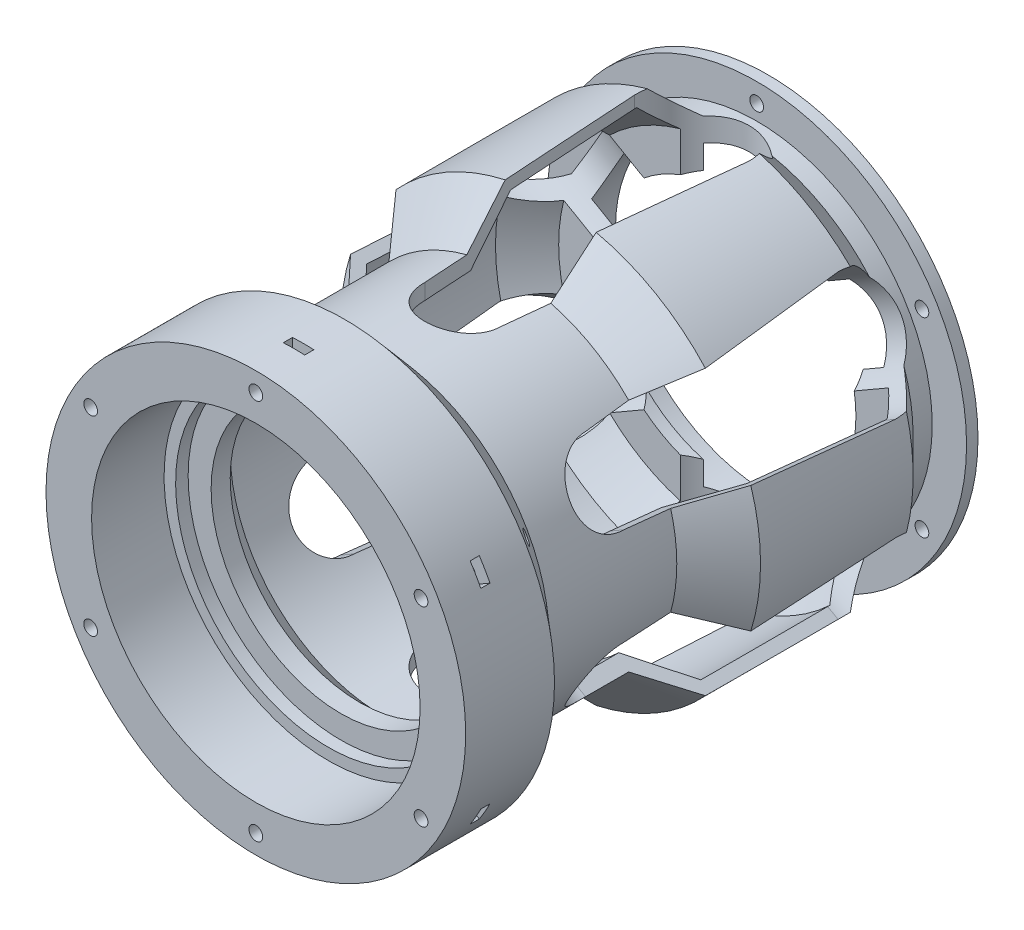
SolidWorks part; units mm, degrees
ref_plane "Front Plane" through (0, 0, 0) normal (0, 0, 1) x (1, 0, 0)
ref_plane "Top Plane" through (0, 0, 0) normal (0, 1, 0) x (1, 0, 0)
ref_plane "Right Plane" through (0, 0, 0) normal (1, 0, 0) x (0, 0, -1)
sketch "Sketch2" plane through (0, 0, 0) normal (0, 1, 0) x (1, 0, 0)
  line L0 (0, -164.1175) -> (0, 109.4658) construction
  line L1 (-106.4732, 0) -> (104.2682, 0) construction
  line L2 (55, 0) -> (40.025, 0)
  line L3 (40.025, 0) -> (40.025, -8)
  line L7 (40.025, -112) -> (40.025, -115.28)
  line L8 (40.025, -115.28) -> (43.05, -115.28)
  line L9 (43.05, -115.28) -> (43.05, -134.28)
  line L10 (43.05, -134.28) -> (55, -134.28)
  line L11 (55, -134.28) -> (55, -111)
  line L15 (55, -3) -> (55, 0)
  line L16 (40.025, -112) -> (34, -112)
  line L17 (34, -112) -> (34, -107)
  line L18 (34, -8) -> (40.025, -8)
  line L19 (55, -111) -> (44.025, -101.4991)
  line L20 (34, -107) -> (40.025, -100.975)
  line L21 (40.025, -100.975) -> (40.025, -66.9026)
  line L23 (34, -11) -> (34, -8)
  line L24 (55, -3) -> (46, -3)
  line L25 (46, -3) -> (46, -8)
  line L26 (46, -8) -> (55, -17)
  line L27 (55, -17) -> (55, -57)
  line L28 (55, -57) -> (44.025, -67.975)
  line L29 (44.025, -67.975) -> (44.025, -101.4991)
  line L30 (34, -11) -> (43.9026, -11)
  line L31 (43.9026, -11) -> (52, -19.466)
  line L32 (52, -19.466) -> (52, -55.4489)
  line L33 (52, -55.4489) -> (40.025, -66.9026)
  dimension "D2" = 68
  dimension "D3" = 40.025
  dimension "D4" = 8
  dimension "D5" = 3.28
  dimension "D6" = 55
  dimension "D7" = 19
  dimension "D8" = 43.05
  dimension "D9" = 3
  dimension "D10" = 40.025
  dimension "D11" = 5
  dimension "D12" = 104
  dimension "D13" = 55
  dimension "D14" = 5
  dimension "D15" = 46
  dimension "D16" = 3
  dimension "D17" = 135
  dimension "D18" = 55
  dimension "D19" = 112
  dimension "D20" = 40
  dimension "D21" = 3
  dimension "D22" = 4
revolve "Revolve1" add sketch "Sketch2" angle 360 about L0
sketch "Sketch3" plane through (0, 0, 134.28) normal (0, 0, 1) x (1, 0, 0)
  line L0 (0, 57.5768) -> (0, -57.0977) construction
  circle A0 centre (0, 50) radius 1.8
  circle A1 centre (43.3013, 25) radius 1.8
  circle A2 centre (43.3013, -25) radius 1.8
  circle A3 centre (0, -50) radius 1.8
  circle A4 centre (-43.3013, -25) radius 1.8
  circle A5 centre (-43.3013, 25) radius 1.8
  point P17 (0, 0)
  dimension "D1" = 3.6
  dimension "D2" = 50
  dimension "D3" = 6
extrude "Cut-Extrude1" cut sketch "Sketch3" against normal through all
sketch "Sketch4" plane through (0, 0, 115.28) normal (0, 0, 1) x (1, 0, 0)
  line L0 (0, 59.4934) -> (0, -58.3754) construction
  line L1 (-2.45, 44.9333) -> (-2.45, 39.9499)
  line L2 (2.45, 44.9333) -> (2.45, 39.9499)
  circle A0 centre (0, 0) radius 40.025 construction
  circle A1 centre (0, 0) radius 43.05
  arc A3 (2.45, 39.9499) -> (-2.45, 39.9499) centre (0, 0) ccw
  circle A6 centre (0, 0) radius 43.05
  circle M5 centre (0, 0) radius 43.05
  circle M6 centre (0, 0) radius 40.025
  dimension "D2" = 2.45
  dimension "D1" = 0
extrude "Boss-Extrude1" add sketch "Sketch4" along normal blind 5 contours L0 A6 L1 M6 | L0 A3 L2 M5
ref_plane "Plane1" through (0, 0, 124.28) normal (0, 0, 1) x (1, 0, 0)
sketch "Sketch5" plane through (0, 0, 124.28) normal (0, 0, 1) x (1, 0, 0)
  line L0 (0, 71.302) -> (0, -65.8547) construction
  line L1 (-25.8624, 50) -> (32.4005, 50) construction
  line L2 (-2.8, 58.331) -> (-2.8, 47.2)
  line L3 (-2.8, 47.2) -> (2.8, 47.2)
  line L4 (2.8, 47.2) -> (2.8, 58.331)
  line L5 (2.8, 58.331) -> (-2.8, 58.331)
  line L6 (51.9161, 26.7406) -> (49.1161, 31.5904)
  line L7 (49.1161, 31.5904) -> (39.4764, 26.0249)
  line L8 (39.4764, 26.0249) -> (42.2764, 21.1751)
  line L9 (42.2764, 21.1751) -> (51.9161, 26.7406)
  line L10 (49.1161, -31.5904) -> (51.9161, -26.7406)
  line L11 (51.9161, -26.7406) -> (42.2764, -21.1751)
  line L12 (42.2764, -21.1751) -> (39.4764, -26.0249)
  line L13 (39.4764, -26.0249) -> (49.1161, -31.5904)
  line L14 (-2.8, -58.331) -> (2.8, -58.331)
  line L15 (2.8, -58.331) -> (2.8, -47.2)
  line L16 (2.8, -47.2) -> (-2.8, -47.2)
  line L17 (-2.8, -47.2) -> (-2.8, -58.331)
  line L18 (-51.9161, -26.7406) -> (-49.1161, -31.5904)
  line L19 (-49.1161, -31.5904) -> (-39.4764, -26.0249)
  line L20 (-39.4764, -26.0249) -> (-42.2764, -21.1751)
  line L21 (-42.2764, -21.1751) -> (-51.9161, -26.7406)
  line L22 (-49.1161, 31.5904) -> (-51.9161, 26.7406)
  line L23 (-51.9161, 26.7406) -> (-42.2764, 21.1751)
  line L24 (-42.2764, 21.1751) -> (-39.4764, 26.0249)
  line L25 (-39.4764, 26.0249) -> (-49.1161, 31.5904)
  point P33 (0, 0)
  dimension "D1" = 2.8
  dimension "D2" = 5.6
  dimension "D3" = 2.8
  dimension "D4" = 6
extrude "Cut-Extrude2" cut sketch "Sketch5" against normal blind 2.4
sketch "Sketch6" plane through (0, 0, 0) normal (0, 1, 0) x (1, 0, 0)
  line L0 (0, 38.0695) -> (0, -150.3703) construction
  line L1 (-15, -20) -> (-10, -80)
  line L2 (15, -20) -> (10, -80)
  arc A0 (15, -20) -> (-15, -20) centre (0, -20) ccw
  arc A1 (-10, -80) -> (10, -80) centre (0, -80) ccw
  dimension "D1" = 30
  dimension "D3" = 20
  dimension "D4" = 60
  dimension "D2" = 20
extrude "Cut-Extrude3" cut sketch "Sketch6" against normal through all both and the other way through all
pattern_circular "CirPattern1" count 3 over 360 about axis through (0, 0, 0) along (0, 0, 1) of "Cut-Extrude3"
